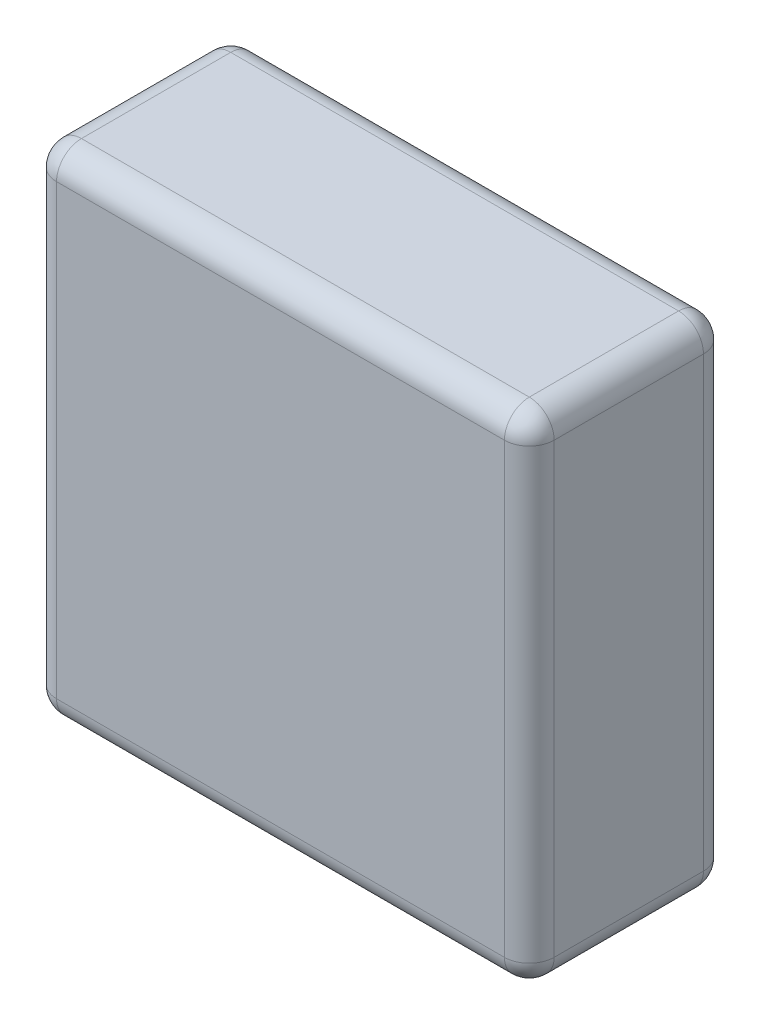
SolidWorks part; units mm, degrees
ref_plane "Plan de face" through (0, 0, 0) normal (0, 0, 1) x (1, 0, 0)
ref_plane "Plan de dessus" through (0, 0, 0) normal (0, 1, 0) x (1, 0, 0)
ref_plane "Plan de droite" through (0, 0, 0) normal (1, 0, 0) x (0, 0, -1)
sketch "Esquisse1" plane through (0, 0, 0) normal (0, 0, 1) x (1, 0, 0)
  line L1 (0, 0) -> (10, 0)
  line L2 (0, 0) -> (0, -10)
  line L3 (0, -10) -> (10, -10)
  line L4 (10, 0) -> (10, -10)
  dimension "D1" = 10
  dimension "D2" = 10
extrude "Boss.-Extru.1" add sketch "Esquisse1" along normal blind 4
fillet "Congé1" radius 0.5 12 edges at (0, 0, 2) (0, -10, 2) (10, -10, 2) (10, 0, 2) (5, -10, 0) (10, -5, 0) (5, 0, 0) (0, -5, 0) (5, 0, 4) (10, -5, 4) (5, -10, 4) (0, -5, 4)
